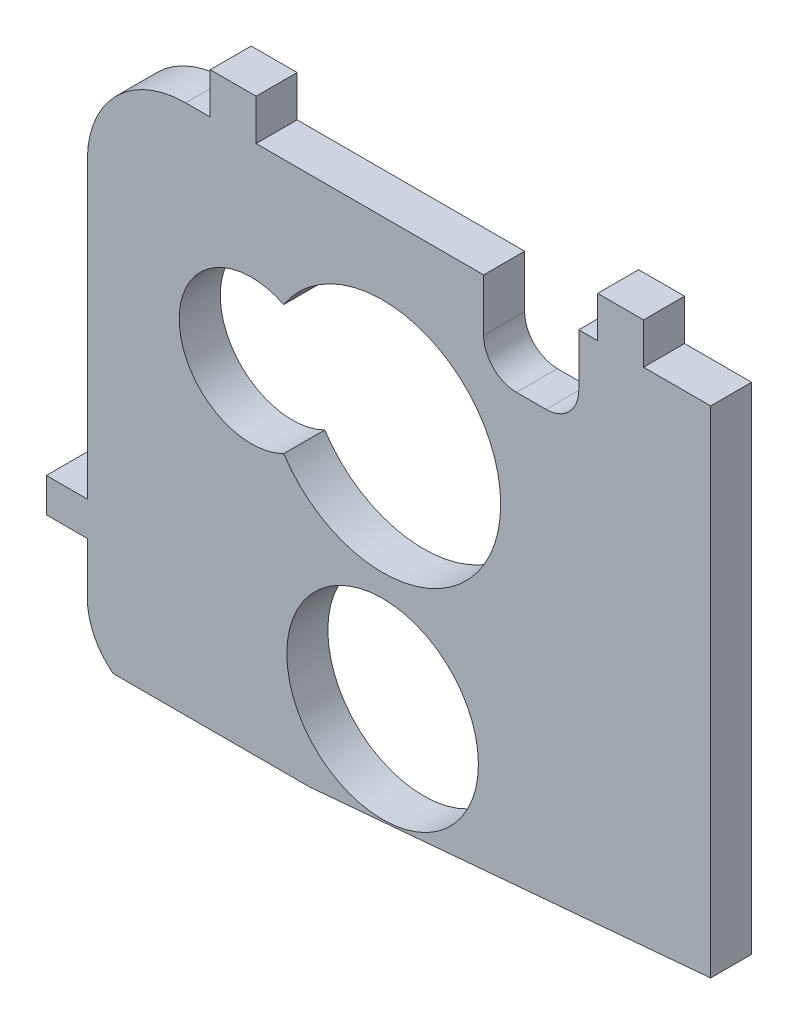
SolidWorks part; units mm, degrees
material "Balsa"
ref_plane "Front Plane" through (0, 0, 0) normal (0, 0, 1) x (1, 0, 0)
ref_plane "Top Plane" through (0, 0, 0) normal (0, 1, 0) x (1, 0, 0)
ref_plane "Right Plane" through (0, 0, 0) normal (1, 0, 0) x (0, 0, -1)
sketch "Sketch1" plane through (0, 0, 0) normal (0, 0, 1) x (1, 0, 0)
  line L0 (0, -1000.1535) -> (0, 48999.8465) construction
  line L1 (-2.8233, -4.0284) -> (-10.4313, -4.0284)
  line L2 (-1000, 0) -> (49000, 0) construction
  line L3 (12.7, 16.51) -> (-7.62, 16.51)
  line L4 (12.7, 16.51) -> (12.7, -2.6702)
  line L5 (8.3256, 18.0975) -> (10.1036, 18.0975)
  line L6 (12.7, -2.6702) -> (-8.6686, -4.5398)
  line L7 (-11.43, 12.7) -> (-11.43, -2.0094)
  line L8 (-6.6744, 16.51) -> (-4.8964, 16.51)
  line L9 (-6.6744, 16.51) -> (-6.6744, 18.0975)
  line L10 (-6.6744, 18.0975) -> (-4.8964, 18.0975)
  line L11 (-4.8964, 16.51) -> (-4.8964, 18.0975)
  line L12 (-11.43, 0) -> (-13.0175, 0)
  line L13 (-11.43, 0) -> (-11.43, 1.3208)
  line L14 (-11.43, 1.3208) -> (-13.0175, 1.3208)
  line L15 (-13.0175, 0) -> (-13.0175, 1.3208)
  line L16 (10.1036, 16.51) -> (10.1036, 18.0975)
  line L17 (8.3256, 16.51) -> (10.1036, 16.51)
  line L18 (8.3256, 16.51) -> (8.3256, 18.0975)
  circle A0 centre (0, 0) radius 3.7084
  arc A1 (-3.829, 6.6457) -> (-3.829, 11.6423) centre (0, 9.144) ccw
  arc A2 (-3.829, 11.6423) -> (-3.829, 6.6457) centre (-5.08, 9.144) ccw
  arc A3 (-7.62, 16.51) -> (-11.43, 12.7) centre (-7.62, 12.7) ccw
  arc A4 (-8.6686, -4.5398) -> (-11.43, -2.0094) centre (-8.89, -2.0094) cw
  dimension "D1" = 7.4168
  dimension "D4" = 7.366
  dimension "D3" = 9.144
  dimension "D5" = 5.588
  dimension "D9" = 3.81
  dimension "D10" = 11.43
  dimension "D14" = 1.5875
  dimension "D12" = 2.54
  dimension "D2" = 12.7
  dimension "D6" = 9.144
  dimension "D7" = 5.08
  dimension "D8" = 6.35
  dimension "D11" = 5
  dimension "D13" = 3.767
  dimension "D15" = 1.778
  dimension "D16" = 1.5875
  dimension "D17" = 1.3208
  dimension "D18" = 1.778
  dimension "D19" = 1.5875
extrude "Boss-Extrude1" add sketch "Sketch1" along normal blind 1.5875
sketch "Sketch3" plane through (0, 0, 1.5875) normal (0, 0, 1) x (1, 0, 0)
  line L0 (6.8073, 16.51) -> (6.8073, 18.0975) construction
  line L1 (6.8073, 16.51) -> (6.8073, 18.0975) construction
  line L2 (4.6991, 18.0975) -> (4.6991, 16.51) construction
  line L3 (4.6991, 18.0975) -> (4.6991, 16.51) construction
  line L4 (8.3256, 16.51) -> (-4.8964, 16.51) construction
  line L5 (7.5947, 16.51) -> (3.9117, 16.51)
  line L6 (7.5947, 16.51) -> (7.5947, 13.208)
  line L7 (7.5947, 13.208) -> (3.9117, 13.208)
  line L8 (3.9117, 16.51) -> (3.9117, 13.208)
  line L9 (6.8073, 17.6426) -> (7.5947, 17.6426) construction
  line L10 (4.6991, 17.6426) -> (3.9117, 17.6426) construction
  line L11 (3.9117, 17.6426) -> (3.9117, 16.51) construction
  line L12 (7.5947, 17.6426) -> (7.5947, 16.51) construction
  dimension "D1" = 3.302
  dimension "D2" = 3.683
extrude "Cut-Extrude1" cut sketch "Sketch3" against normal through all
fillet "Fillet1" radius 1.27 2 edges at (7.5947, 13.208, 0.7937) (3.9117, 13.208, 0.7937)
